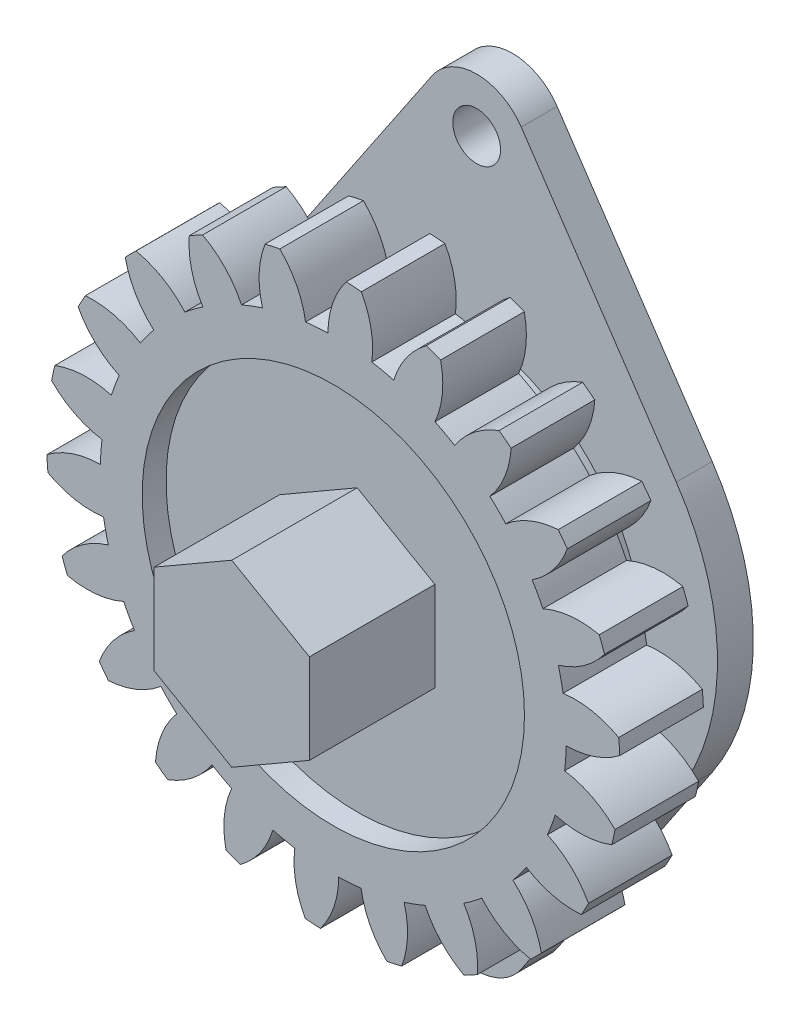
SolidWorks part; units mm, degrees
ref_plane "前视基准面" through (0, 0, 0) normal (0, 0, 1) x (1, 0, 0)
ref_plane "上视基准面" through (0, 0, 0) normal (0, 1, 0) x (1, 0, 0)
ref_plane "右视基准面" through (0, 0, 0) normal (1, 0, 0) x (0, 0, -1)
sketch "草图1" plane through (0, 0, 0) normal (0, 0, 1) x (1, 0, 0)
  line L0 (0, 0) -> (0, 24) construction
  line L1 (0, 0) -> (8.2085, 22.5526) construction
  line L2 (0, 22) -> (7.0707, 19.4265) construction
  line L3 (0, 0) -> (0.4535, 19.4947) construction
  line L4 (0, 0) -> (3.2226, 19.2319) construction
  circle A0 centre (0, 0) radius 24 construction
  circle A1 centre (0, 0) radius 22 construction
  circle A2 centre (0, 0) radius 19.5 construction
  arc A4 (1.0773, 23.9758) -> (-0.4535, 19.4947) centre (7.0707, 19.4265) ccw
  arc A5 (-1.0773, 23.9758) -> (0.4535, 19.4947) centre (-7.0707, 19.4265) cw construction
  arc A6 (2.3451, 23.8852) -> (3.2226, 19.2319) centre (-4.2347, 20.2349) cw
  arc A7 (1.0773, 23.9758) -> (2.3451, 23.8852) centre (0, 0) cw
  arc A8 (-0.4535, 19.4947) -> (3.2226, 19.2319) centre (0, 0) cw
  dimension "D1" = 48
  dimension "D2" = 44
  dimension "D3" = 39
  dimension "D5" = 2
  dimension "D4" = 20
  dimension "D6" = 8.18
  dimension "D7" = 19.5
extrude "凸台-拉伸1" add sketch "草图1" along normal mid plane 7
sketch "草图2" plane through (0, 0, 3.5) normal (0, 0, 1) x (1, 0, 0)
  circle A0 centre (0, 0) radius 19.5
extrude "凸台-拉伸2" add sketch "草图2" against normal blind 7
pattern_circular "阵列(圆周)1" count 22 over 360 about axis through (0, 0, 0) along (0, 0, 1) of "凸台-拉伸1"
sketch "草图3" plane through (0, 0, 3.5) normal (0, 0, 1) x (1, 0, 0)
  circle A0 centre (0, 0) radius 16
  dimension "D1" = 32
extrude "切除-拉伸1" cut sketch "草图3" against normal blind 2
sketch "草图4" plane through (0, 0, -3.5) normal (0, 0, -1) x (-1, 0, 0)
  circle A0 centre (0, 0) radius 16
  dimension "D1" = 32
extrude "凸台-拉伸3" add sketch "草图4" along normal blind 3
sketch "草图5" plane through (0, 0, -6.5) normal (0, 0, -1) x (-1, 0, 0)
  circle A0 centre (0, 0) radius 6
  dimension "D1" = 12
extrude "凸台-拉伸4" add sketch "草图5" along normal blind 2
sketch "草图6" plane through (0, 0, -8.5) normal (0, 0, -1) x (-1, 0, 0)
  line L0 (0, -32.5) -> (0, 32.5) construction
  line L1 (-3.7309, 30.516) -> (-16.7104, 11.2688)
  line L2 (3.7309, 30.516) -> (16.7104, 11.2688)
  line L3 (-16.7104, -11.2688) -> (-3.7309, -30.516)
  line L4 (16.7104, -11.2688) -> (3.7309, -30.516)
  arc A0 (-16.7104, 11.2688) -> (-16.7104, -11.2688) centre (0, 0) ccw
  arc A1 (3.7309, 30.516) -> (-3.7309, 30.516) centre (0, 28) ccw
  arc A2 (-3.7309, -30.516) -> (3.7309, -30.516) centre (0, -28) ccw
  circle A3 centre (0, 28) radius 2
  circle A4 centre (0, -28) radius 2
  arc A5 (16.7104, -11.2688) -> (16.7104, 11.2688) centre (0, 0) ccw
  point P6 (0, 0)
  dimension "D1" = 40.31
  dimension "D2" = 65
  dimension "D3" = 56
  dimension "D4" = 4
extrude "凸台-拉伸5" add sketch "草图6" along normal blind 3
sketch "草图7" plane through (0, 0, -11.5) normal (0, 0, -1) x (-1, 0, 0)
  circle A0 centre (0, 0) radius 5
  dimension "D1" = 10
extrude "凸台-拉伸6" add sketch "草图7" along normal blind 2.5
sketch "草图8" plane through (0, 0, 1.5) normal (0, 0, 1) x (1, 0, 0)
  line L1 (0, 7.5056) -> (-6.5, 3.7528)
  line L2 (-6.5, 3.7528) -> (-6.5, -3.7528)
  line L3 (-6.5, -3.7528) -> (0, -7.5056)
  line L4 (0, -7.5056) -> (6.5, -3.7528)
  line L5 (6.5, -3.7528) -> (6.5, 3.7528)
  line L6 (6.5, 3.7528) -> (0, 7.5056)
  circle A0 centre (0, 0) radius 6.5 construction
  dimension "D1" = 13
extrude "凸台-拉伸7" add sketch "草图8" along normal offset from surface (10.5 mm away) 26 up to face at (-5, 0, -14)
